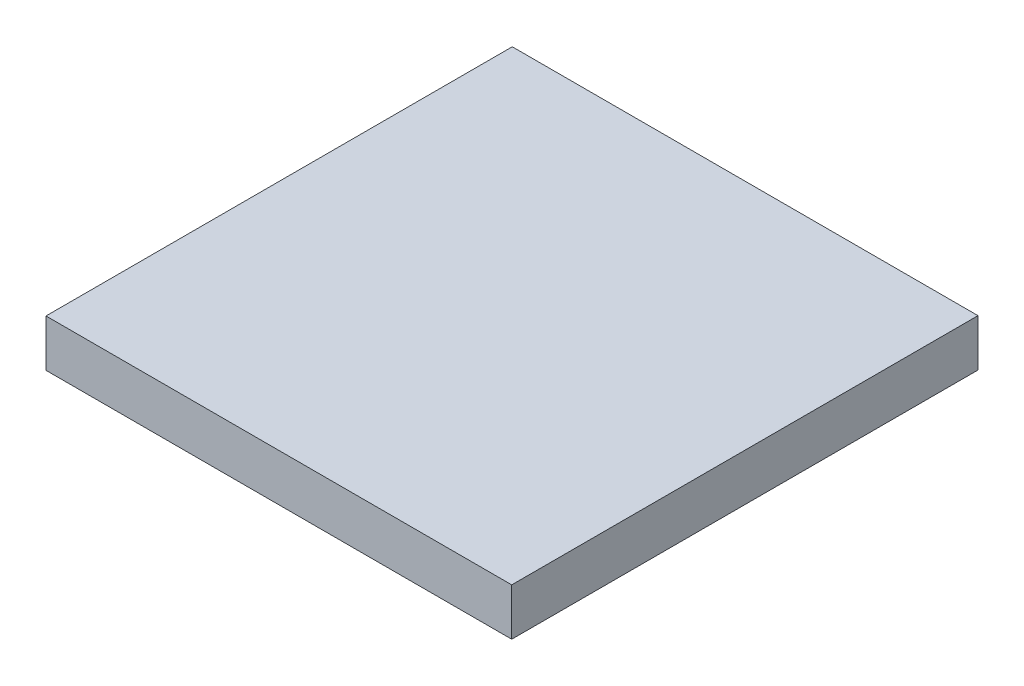
SolidWorks part; units mm, degrees
ref_plane "Front Plane" through (0, 0, 0) normal (0, 0, 1) x (1, 0, 0)
ref_plane "Top Plane" through (0, 0, 0) normal (0, 1, 0) x (1, 0, 0)
ref_plane "Right Plane" through (0, 0, 0) normal (1, 0, 0) x (0, 0, -1)
sketch "Sketch1" plane through (0, 0, 0) normal (0, 1, 0) x (1, 0, 0)
  line L1 (0, 0) -> (29.654, 0)
  line L2 (0, 0) -> (0, -29.6887)
  line L3 (0, -29.6887) -> (29.654, -29.6887)
  line L4 (29.654, 0) -> (29.654, -29.6887)
extrude "Boss-Extrude1" add sketch "Sketch1" along normal blind 3
scale "Scale1" scale about centroid uniform scaling yes scale factor 0.3
